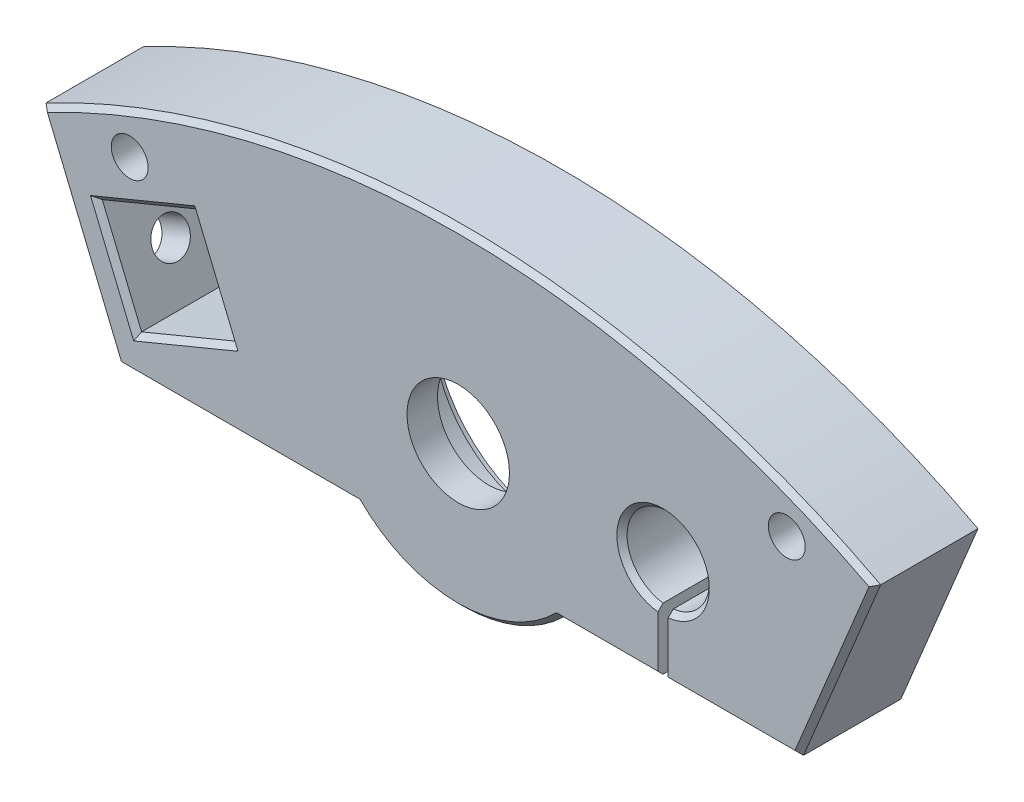
SolidWorks part; units mm, degrees
ref_plane "Front Plane" through (0, 0, 0) normal (0, 0, 1) x (1, 0, 0)
ref_plane "Top Plane" through (0, 0, 0) normal (0, 1, 0) x (1, 0, 0)
ref_plane "Right Plane" through (0, 0, 0) normal (1, 0, 0) x (0, 0, -1)
sketch "Sketch1" plane through (0, 0, 0) normal (0, 0, 1) x (1, 0, 0)
  line L0 (-46.9014, 0) -> (43.5211, 0) construction
  line L1 (0, 38.5211) -> (0, -80.4339) construction
  line L2 (-33.5349, -69.25) -> (36.7559, -69.25) construction
  line L3 (0, -69.25) -> (-37.9703, 22.4183) construction
  line L4 (-40.7467, 8.1836) -> (-33.2148, -10)
  line L5 (-25.9885, 6.5901) -> (-35.2504, 2.7537)
  line L6 (-35.2504, 2.7537) -> (-31.414, -6.5082)
  line L7 (-31.414, -6.5082) -> (-22.1521, -2.6718)
  line L8 (-22.1521, -2.6718) -> (-25.9885, 6.5901)
  line L9 (-33.2148, -10) -> (-9.798, -10)
  line L10 (33.2148, -10) -> (20.5, -10)
  line L11 (40.7467, 8.1836) -> (33.2148, -10)
  line L12 (20, 7.6656) -> (20, -13.8845) construction
  line L13 (19.5, -3.9812) -> (19.5, -10)
  line L14 (20.5, -3.9812) -> (20.5, -10)
  line L15 (19.5, -10) -> (9.798, -10)
  arc A0 (20.5, -3.9812) -> (19.5, -3.9812) centre (20, 0) ccw
  circle A1 centre (-28.7013, 0.041) radius 5.0125 construction
  arc A2 (40.7467, 8.1836) -> (-40.7467, 8.1836) centre (0, -69.25) ccw
  arc A5 (-9.798, -10) -> (9.798, -10) centre (0, 0) ccw
  circle A6 centre (0, 0) radius 5
  circle A7 centre (-32.0765, 8.1894) radius 1.8
  circle A8 centre (32.0765, 8.1894) radius 1.8
  dimension "D1" = 20
  dimension "D2" = 8.025
  dimension "D7" = 75
  dimension "D8" = 175
  dimension "D9" = 3
  dimension "D10" = 14
  dimension "D12" = 10
  dimension "D13" = 3.6
  dimension "D14" = 32.0765
  dimension "D3" = 69.25
  dimension "D4" = 22.5
  dimension "D5" = 10.025
  dimension "D6" = 90
  dimension "D11" = 10
  dimension "D15" = 0.5
extrude "Boss-Extrude1" add sketch "Sketch1" along normal blind 10
sketch "Sketch3" plane through (0, 0, 0) normal (0, 0, -1) x (-1, 0, 0)
  circle A0 centre (0, 0) radius 11.025
  dimension "D1" = 22.05
extrude "Cut-Extrude2" cut sketch "Sketch3" against normal blind 7.025
sketch "Sketch4" plane through (0, 0, 0) normal (0, 0, -1) x (-1, 0, 0)
  circle A0 centre (0, 0) radius 12.525
  dimension "D1" = 25.05
extrude "Cut-Extrude3" cut sketch "Sketch4" against normal blind 1.425
chamfer "Chamfer1" distance 0.5 5 edges at (-33.3322, -1.8772, 10) (-26.7831, -4.59, 10) (-24.0703, 1.9592, 10) (-30.6195, 4.6719, 10) (20, 4.0125, 10)
sketch "Sketch5" plane through (-29.1145, -12.0596, 0) normal (0.9239, 0.3827, 0) x (0, 0, -1)
  line L5 (-9.5, 16.0338) -> (0, 16.0338) construction
  line L6 (0, 16.0338) -> (0, 6.0088) construction
  circle A0 centre (-4.75, 11.0188) radius 1.8
  dimension "D1" = 3.6
  dimension "D2" = 5.015
  dimension "D3" = 4.75
extrude "Cut-Extrude4" cut sketch "Sketch5" against normal blind 10
chamfer "Chamfer2" distance 0.5 angle 45 7 edges at (26.8574, -10, 10) (36.9808, -0.9082, 10) (14.649, -10, 10) (0, -14, 10) (-21.5064, -10, 10) (-36.9808, -0.9082, 10) (0, 18.25, 10)
